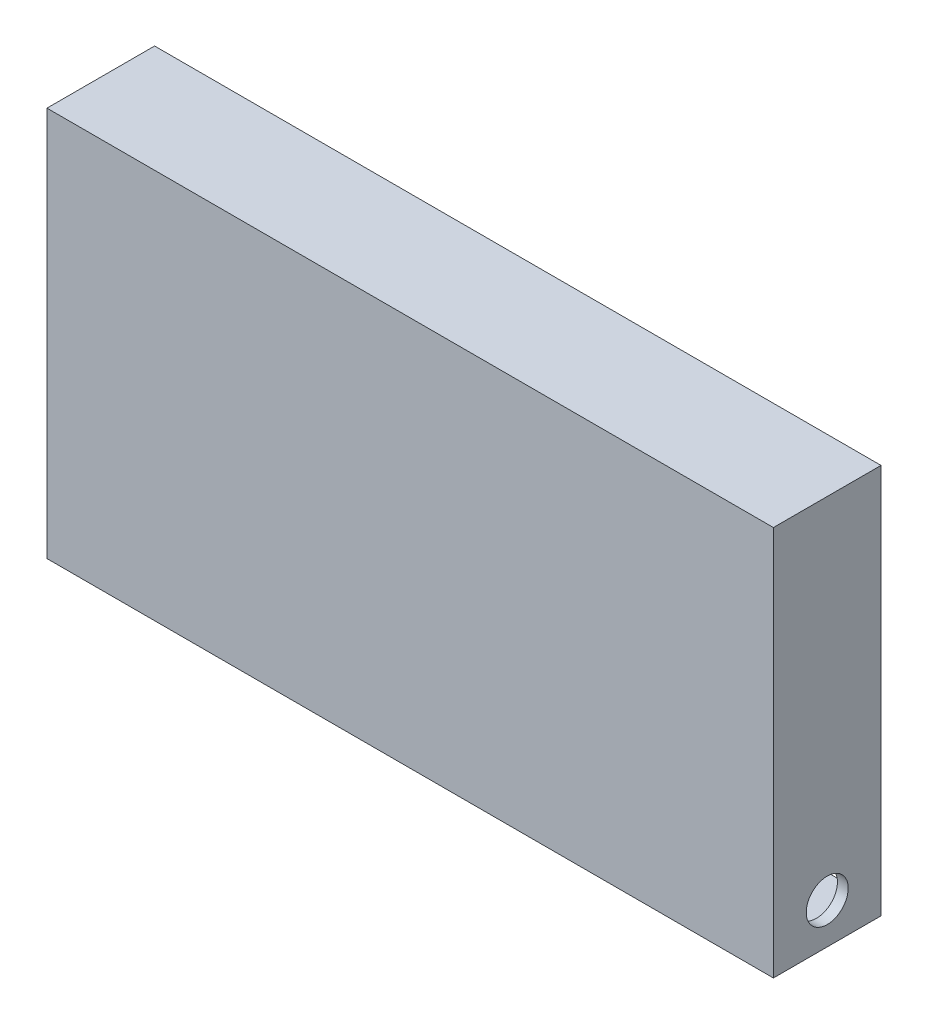
SolidWorks part; units mm, degrees
ref_plane "Front Plane" through (0, 0, 0) normal (0, 0, 1) x (1, 0, 0)
ref_plane "Top Plane" through (0, 0, 0) normal (0, 1, 0) x (1, 0, 0)
ref_plane "Right Plane" through (0, 0, 0) normal (1, 0, 0) x (0, 0, -1)
sketch "Sketch3" plane through (0, 0, 0) normal (0, 0, 1) x (1, 0, 0)
  line L1 (-67.5, -36.25) -> (67.5, -36.25)
  line L2 (-67.5, -36.25) -> (-67.5, 36.25)
  line L3 (-67.5, 36.25) -> (67.5, 36.25)
  line L4 (67.5, -36.25) -> (67.5, 36.25)
  line L5 (-67.5, -36.25) -> (67.5, 36.25) construction
  line L6 (-67.5, 36.25) -> (67.5, -36.25) construction
  point P0 (0, 0)
  dimension "D1" = 135
  dimension "D2" = 72.5
extrude "Boss-Extrude1" add sketch "Sketch3" along normal blind 20
sketch "Sketch4" plane through (0, 0, 0) normal (0, 0, -1) x (-1, 0, 0)
  line L0 (-67.5, 36.25) -> (67.5, 36.25) construction
  line L1 (-65.5, 34.25) -> (65.5, 34.25)
  line L2 (-65.5, 34.25) -> (-65.5, -34.25)
  line L3 (-65.5, -34.25) -> (65.5, -34.25)
  line L4 (65.5, 34.25) -> (65.5, -34.25)
  line L5 (-65.5, 34.25) -> (65.5, -34.25) construction
  line L6 (-65.5, -34.25) -> (65.5, 34.25) construction
  line L7 (-67.5, -36.25) -> (-67.5, 36.25) construction
  point P0 (0, 0)
  dimension "D1" = 2
  dimension "D2" = 2
extrude "Cut-Extrude1" cut sketch "Sketch4" against normal blind 18
sketch "Sketch5" plane through (0, 0, 18) normal (0, 0, -1) x (-1, 0, 0)
  line L0 (-65.5, 34.25) -> (-65.5, -34.25) construction
  line L1 (-65.5, 21.75) -> (-43.7, 21.75)
  line L2 (-65.5, 21.75) -> (-65.5, -21.75)
  line L3 (-65.5, -21.75) -> (-43.7, -21.75)
  line L4 (-43.7, 21.75) -> (-43.7, -21.75)
  line L5 (-65.5, -34.25) -> (65.5, -34.25) construction
  dimension "D1" = 21.8
  dimension "D2" = 43.5
  dimension "D3" = 12.5
sketch "Sketch6" plane through (0, 0, 18) normal (0, 0, -1) x (-1, 0, 0)
  line L0 (-65.5, 34.25) -> (-65.5, -34.25) construction
  line L1 (-65.5, 22.95) -> (-42.5, 22.95)
  line L2 (-65.5, 22.95) -> (-65.5, -22.95)
  line L3 (-65.5, -22.95) -> (-42.5, -22.95)
  line L4 (-42.5, 22.95) -> (-42.5, -22.95)
  line L5 (-65.5, 21.75) -> (-43.7, 21.75) construction
  line L6 (-43.7, 21.75) -> (-43.7, -21.75) construction
  line L7 (-65.5, -21.75) -> (-43.7, -21.75) construction
  dimension "D1" = 1.2
  dimension "D2" = 1.2
  dimension "D3" = 1.2
extrude "Boss-Extrude2" add sketch "Sketch6" along normal blind 8
extrude "Cut-Extrude2" cut sketch "Sketch5" along direction (0, 0, -1) on the side of the normal blind 18
sketch "Sketch7" plane through (0, 0, 18) normal (0, 0, -1) x (-1, 0, 0)
  line L1 (-65.5, -34.25) -> (65.5, -34.25) construction
  line L2 (-42.5, -22.95) -> (-43.7, -22.95)
  line L3 (-42.5, -22.95) -> (-42.5, -31.25)
  line L4 (-42.5, -31.25) -> (-43.7, -31.25)
  line L5 (-43.7, -22.95) -> (-43.7, -31.25)
  line L6 (65.5, 34.25) -> (-65.5, 34.25) construction
  line L7 (-42.5, 22.95) -> (-43.7, 22.95)
  line L8 (-42.5, 22.95) -> (-42.5, 34.25)
  line L9 (-42.5, 34.25) -> (-43.7, 34.25)
  line L10 (-43.7, 22.95) -> (-43.7, 34.25)
  dimension "D1" = 1.2
  dimension "D2" = 3
  dimension "D3" = 1.2
extrude "Boss-Extrude5" add sketch "Sketch7" along normal up to vertex
sketch "Sketch9" plane through (0, 0, 18) normal (0, 0, -1) x (-1, 0, 0)
  line L0 (65.5, 34.25) -> (-42.5, 34.25) construction
  line L1 (24.95, 34.25) -> (26.15, 34.25)
  line L2 (24.95, 34.25) -> (24.95, -31.25)
  line L3 (24.95, -31.25) -> (26.15, -31.25)
  line L4 (26.15, 34.25) -> (26.15, -31.25)
  line L5 (-65.5, -34.25) -> (65.5, -34.25) construction
  line L6 (-42.5, -31.25) -> (-42.5, 34.25) construction
  dimension "D1" = 3
  dimension "D2" = 1.2
  dimension "D3" = 67.45
extrude "Boss-Extrude6" add sketch "Sketch9" along normal up to surface (8 mm away) up to face at (50.7667, 0.5, 10)
sketch "Sketch10" plane through (0, 0, 18) normal (0, 0, -1) x (-1, 0, 0)
  line L0 (26.15, -31.25) -> (26.15, 34.25) construction
  line L1 (26.15, 16.8) -> (51.75, 16.8)
  line L2 (26.15, 16.8) -> (26.15, -16.8)
  line L3 (26.15, -16.8) -> (51.75, -16.8)
  line L4 (51.75, 16.8) -> (51.75, -16.8)
  line L5 (65.5, 34.25) -> (26.15, 34.25) construction
  line L6 (-65.5, -34.25) -> (65.5, -34.25) construction
  dimension "D1" = 25.6
  dimension "D2" = 33.6
  dimension "D3" = 17.45
  dimension "D4" = 17.45
sketch "Sketch11" plane through (0, 0, 18) normal (0, 0, -1) x (-1, 0, 0)
  line L0 (26.15, -31.25) -> (26.15, 34.25) construction
  line L1 (26.15, 18) -> (52.95, 18)
  line L2 (26.15, 18) -> (26.15, -18)
  line L3 (26.15, -18) -> (52.95, -18)
  line L4 (52.95, 18) -> (52.95, -18)
  line L5 (26.15, 16.8) -> (51.75, 16.8) construction
  line L6 (26.15, -16.8) -> (51.75, -16.8) construction
  line L7 (51.75, 16.8) -> (51.75, -16.8) construction
  dimension "D1" = 1.2
  dimension "D2" = 1.2
  dimension "D3" = 1.2
extrude "Boss-Extrude7" add sketch "Sketch11" along normal up to surface (8 mm away) up to face at (-25.55, 1.5, 10)
extrude "Cut-Extrude3" cut sketch "Sketch10" along normal up to surface (8 mm away) up to face at (-32.55, 0.75, 10)
sketch "Sketch13" plane through (-52.95, 0, 0) normal (-1, 0, 0) x (0, 0, 1)
  line L1 (10, 16.8) -> (18, 16.8)
  line L2 (10, 16.8) -> (10, -16.8)
  line L3 (10, -16.8) -> (18, -16.8)
  line L4 (18, 16.8) -> (18, -16.8)
  point P4 (18.5594, -16.9521)
  point P5 (10.135, -18.0619)
  point P6 (0, 0)
  point P7 (0, 0)
  point P10 (0, 0)
  point P11 (0, 0)
  point P13 (0, 0)
  point P15 (0, 0)
  point P17 (0, 0)
extrude "Cut-Extrude4" cut sketch "Sketch13" against normal up to surface (1.2 mm away) up to face at (-51.75, 0, 14)
sketch "Sketch14" plane through (67.5, 0, 0) normal (1, 0, 0) x (0, 0, -1)
  line L0 (-20, -36.25) -> (0, -36.25) construction
  line L1 (-20, -36.25) -> (-20, 36.25) construction
  line L2 (0, -36.25) -> (0, 36.25) construction
  circle A0 centre (-10, -28.75) radius 3.9
  point P2 (-10.1196, -28.6268)
  dimension "D1" = 7.8
  dimension "D3" = 10
  dimension "D4" = 10
  dimension "D2" = 7.5
extrude "Cut-Extrude5" cut sketch "Sketch14" against normal up to surface (2 mm away) up to face at (65.5, 0, 12.3333)
sketch "Sketch15" plane through (-67.5, 0, 0) normal (-1, 0, 0) x (0, 0, 1)
  line L0 (20, 36.25) -> (0, 36.25) construction
  line L3 (0, 36.25) -> (0, -36.25) construction
  line L4 (20, 36.25) -> (20, -36.25) construction
  circle A0 centre (10, 26.25) radius 5.4
  circle A1 centre (10, 11.25) radius 5.4
  circle A2 centre (10, -3.75) radius 5.4
  dimension "D1" = 10.8
  dimension "D3" = 10
  dimension "D4" = 10
  dimension "D6" = 10.8
  dimension "D7" = 10.8
  dimension "D2" = 10
  dimension "D5" = 15
  dimension "D8" = 15
extrude "Cut-Extrude6" cut sketch "Sketch15" against normal up to surface (2 mm away) up to face at (-65.5, 0, 9)
sketch "Sketch18" plane through (0, 0, 18) normal (0, 0, -1) x (-1, 0, 0)
  line L0 (26.15, -16.8) -> (52.95, -16.8) construction
  line L1 (37.05, -11.8) -> (42.05, -11.8)
  line L2 (37.05, -11.8) -> (37.05, -16.8)
  line L3 (37.05, -16.8) -> (42.05, -16.8)
  line L4 (42.05, -11.8) -> (42.05, -16.8)
  line L5 (26.15, 16.8) -> (26.15, -16.8) construction
  line L6 (52.95, 16.8) -> (26.15, 16.8) construction
  line L7 (37.05, 16.8) -> (42.05, 16.8)
  line L8 (37.05, 16.8) -> (37.05, 11.8)
  line L9 (37.05, 11.8) -> (42.05, 11.8)
  line L10 (42.05, 16.8) -> (42.05, 11.8)
  dimension "D1" = 5
  dimension "D2" = 5
  dimension "D3" = 10.9
  dimension "D4" = 10.9
  dimension "D5" = 5
  dimension "D6" = 5
  dimension "D7" = 10.9
extrude "Boss-Extrude8" add sketch "Sketch18" along normal blind 5
sketch "Sketch19" plane through (0, 0, 10) normal (0, 0, -1) x (-1, 0, 0)
  line L0 (52.95, -16.8) -> (14.9675, -16.8) construction
  line L1 (52.95, 16.8) -> (15.6954, 16.8) construction
  circle A0 centre (39.6638, -14.3) radius 1.5
  circle A1 centre (39.6638, 14.3) radius 1.5
  dimension "D1" = 3
  dimension "D4" = 3
  dimension "D2" = 2.5
  dimension "D3" = 2.5
extrude "Cut-Extrude7" cut sketch "Sketch19" against normal up to surface (8 mm away) up to face at (54.6, 28.6, 18)
sketch "Sketch20" plane through (0, 0, 18) normal (0, 0, -1) x (-1, 0, 0)
  line L0 (-43.7, -21.75) -> (-43.7, 21.75) construction
  line L1 (-43.7, 18.75) -> (-48.7, 18.75)
  line L2 (-43.7, 18.75) -> (-43.7, 13.75)
  line L3 (-43.7, 13.75) -> (-48.7, 13.75)
  line L4 (-48.7, 18.75) -> (-48.7, 13.75)
  line L5 (-43.7, 21.75) -> (-65.5, 21.75) construction
  line L6 (-65.5, 21.75) -> (-65.5, -21.75) construction
  line L7 (-65.5, -18.75) -> (-60.5, -18.75)
  line L8 (-65.5, -18.75) -> (-65.5, -13.75)
  line L9 (-65.5, -13.75) -> (-60.5, -13.75)
  line L10 (-60.5, -18.75) -> (-60.5, -13.75)
  line L11 (-65.5, -21.75) -> (-43.7, -21.75) construction
  dimension "D1" = 5
  dimension "D2" = 5
  dimension "D3" = 3
  dimension "D4" = 5
  dimension "D5" = 5
  dimension "D6" = 3
extrude "Boss-Extrude9" add sketch "Sketch20" along normal blind 5
sketch "Sketch21" plane through (0, 0, 13) normal (0, 0, -1) x (-1, 0, 0)
  line L0 (-43.7, 18.75) -> (-48.7, 18.75) construction
  line L1 (-60.5, -13.75) -> (-65.5, -13.75) construction
  line L2 (-60.5, -18.75) -> (-60.5, -13.75) construction
  line L3 (-43.7, 21.75) -> (-43.7, -21.75) construction
  circle A0 centre (-46.2, 16.25) radius 1.5
  circle A1 centre (-63, -16.25) radius 1.5
  dimension "D2" = 3
  dimension "D3" = 3
  dimension "D5" = 2.5
  dimension "D6" = 2.5
  dimension "D1" = 2.5
  dimension "D4" = 2.5
extrude "Cut-Extrude8" cut sketch "Sketch21" against normal up to surface (5 mm away) up to face at (54.6, 0, 18)
sketch "Sketch23" plane through (0, 0, 18) normal (0, 0, -1) x (-1, 0, 0)
  line L5 (24.95, 34.25) -> (24.95, -31.25) construction
  line L6 (-42.5, 34.25) -> (-35.5, 34.25)
  line L7 (-42.5, 34.25) -> (-42.5, 27.25)
  line L8 (-42.5, 27.25) -> (-35.5, 27.25)
  line L9 (-35.5, 34.25) -> (-35.5, 27.25)
  line L10 (24.95, 34.25) -> (17.95, 34.25)
  line L11 (24.95, 34.25) -> (24.95, 27.25)
  line L12 (24.95, 27.25) -> (17.95, 27.25)
  line L13 (17.95, 34.25) -> (17.95, 27.25)
  line L14 (24.95, -31.25) -> (17.95, -31.25)
  line L15 (24.95, -31.25) -> (24.95, -24.25)
  line L16 (24.95, -24.25) -> (17.95, -24.25)
  line L17 (17.95, -31.25) -> (17.95, -24.25)
  line L18 (-42.5, -31.25) -> (-42.5, 34.25) construction
  line L19 (-42.5, -31.25) -> (-35.5, -31.25)
  line L20 (-42.5, -31.25) -> (-42.5, -24.25)
  line L21 (-42.5, -24.25) -> (-35.5, -24.25)
  line L22 (-35.5, -31.25) -> (-35.5, -24.25)
  point P22 (0, 0)
  dimension "D1" = 7
  dimension "D2" = 7
  dimension "D3" = 7
  dimension "D4" = 7
  dimension "D5" = 7
  dimension "D6" = 7
  dimension "D7" = 65.5
  dimension "D8" = 7
  dimension "D9" = 7
  dimension "D10" = 65.5
extrude "Boss-Extrude10" add sketch "Sketch23" along normal blind 5
sketch "Sketch24" plane through (0, 0, 13) normal (0, 0, -1) x (-1, 0, 0)
  line L0 (65.5, 34.25) -> (-65.5, 34.25) construction
  line L1 (-42.5, -31.25) -> (-42.5, 34.25) construction
  line L2 (24.95, 34.25) -> (24.95, -31.25) construction
  line L3 (24.95, -24.25) -> (17.95, -24.25) construction
  line L4 (17.95, -24.25) -> (17.95, -31.25) construction
  line L5 (-35.5, -24.25) -> (-42.5, -24.25) construction
  line L6 (-35.5, -31.25) -> (-35.5, -24.25) construction
  circle A0 centre (-39, 30.75) radius 1.5
  circle A1 centre (21.45, 30.75) radius 1.5
  circle A2 centre (21.45, -27.75) radius 1.5
  circle A3 centre (-39, -27.75) radius 1.5
  dimension "D1" = 3
  dimension "D4" = 3
  dimension "D5" = 3.5
  dimension "D6" = 3.5
  dimension "D7" = 3
  dimension "D10" = 3
  dimension "D12" = 3.5
  dimension "D2" = 3.5
  dimension "D3" = 3.5
  dimension "D8" = 3.5
  dimension "D9" = 3.5
  dimension "D11" = 3.5
extrude "Cut-Extrude10" cut sketch "Sketch24" against normal blind 5
